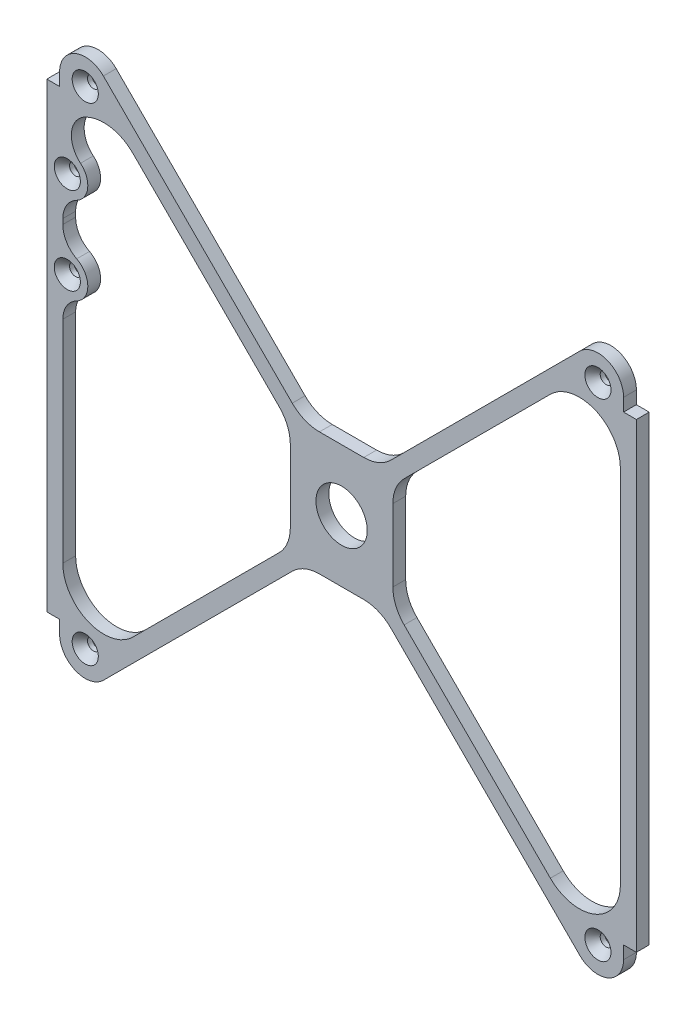
SolidWorks part; units mm, degrees
material "6061-T6 (SS)"
ref_plane "Front Plane" through (0, 0, 0) normal (0, 0, 1) x (1, 0, 0)
ref_plane "Top Plane" through (0, 0, 0) normal (0, 1, 0) x (1, 0, 0)
ref_plane "Right Plane" through (0, 0, 0) normal (1, 0, 0) x (0, 0, -1)
sketch "Sketch1" plane through (0, 0, 0) normal (0, 0, 1) x (1, 0, 0)
  line L0 (0, 0) -> (0, 73.025) construction
  line L1 (0, 0) -> (73.025, 0) construction
  line L2 (73.025, 73.025) -> (73.025, 0) construction
  line L3 (9.4347, 15.24) -> (0, 15.24)
  line L4 (12.7, 12.8926) -> (12.7, 0)
  line L5 (9.4347, 15.24) -> (59.0099, 64.8151)
  line L6 (12.7, 12.8926) -> (51.712, 51.9046)
  line L7 (69.0562, 44.7204) -> (69.0563, 0)
  line L8 (0, 73.025) -> (73.025, 73.025) construction
  line L9 (73.025, 57.15) -> (73.025, 0)
  line L10 (69.85, 60.325) -> (69.85, 57.15)
  line L11 (0, 0) -> (12.7, 0)
  line L12 (0, 15.24) -> (0, 0)
  line L13 (69.0563, 0) -> (73.025, 0)
  line L26 (69.85, 57.15) -> (73.025, 57.15)
  arc A1 (69.85, 60.325) -> (59.0099, 64.8151) centre (63.5, 60.325) ccw
  arc A2 (51.712, 51.9046) -> (69.0562, 44.7204) centre (58.8963, 44.7204) cw
  point P51 (12, 0)
  dimension "D11" = 6.35
  dimension "D5" = 10.16
  dimension "D3" = 12.7
  dimension "D6" = 3.9688
  dimension "D7" = 73.025
  dimension "D10" = 12.7
  dimension "D2" = 73.025
  dimension "D4" = 15.24
  dimension "D9" = 9.525
  dimension "D12" = 135
  dimension "D14" = 3.9688
  dimension "D8" = 15.875
extrude "Boss-Extrude1" add sketch "Sketch1" along normal blind 3.175
sketch "LOCATES-SCREW" plane through (0, 0, 3.175) normal (0, 0, 1) x (1, 0, 0)
  point P0 (63.5, 60.325)
hole_wizard "CSK for #4 Flat Head Machine Screw1" positions "Sketch10" profile "Sketch11" countersink size "#4" standard "ANSI Inch" end condition through all
sketch "Sketch10" plane through (0, 0, 3.175) normal (0, 0, 1) x (1, 0, 0)
  point P0 (63.5, 60.325)
sketch "Sketch11" plane through (63.5, 60.325, 3.175) normal (1, 0, 0) x (0, -1, 0)
  line L0 (0, 0) -> (0, 3.175)
  line L1 (0, 3.175) -> (1.4732, 3.175)
  line L2 (1.4732, 3.175) -> (1.4732, 2.0307)
  line L3 (1.4732, 2.0307) -> (3.2385, 0)
  line L5 (3.2385, 0) -> (0, 0)
  line L6 (-1.4732, 2.0307) -> (-3.2385, 0) construction
  line L11 (0, -6.35) -> (0, 107.95) construction
  dimension "Thru Hole Dia." = 2.9464
  dimension "Thru Hole Depth" = 3.175
  dimension "Near C'Sink Dia." = 6.477
  dimension "Near C'Sink Angle" = 82
mirror "Mirror1" about plane through (0, 0, 0) normal (0, 1, 0) of "CSK for #4 Flat Head Machine Screw1", "Boss-Extrude1"
mirror "Mirror2" about plane through (0, 0, 0) normal (1, 0, 0) of "Mirror1", "Boss-Extrude1", "CSK for #4 Flat Head Machine Screw1"
chamfer "COUNTERSINK" [suppressed] distance 1.27 angle 45
fillet "INTERNAL-SHARPS" radius 9.525 8 edges at (9.4347, 15.24, 1.5875) (-9.4347, 15.24, 1.5875) (12.7, -12.8926, 1.5875) (12.7, 12.8926, 1.5875) (9.4347, -15.24, 1.5875) (-9.4347, -15.24, 1.5875) (-12.7, -12.8926, 1.5875) (-12.7, 12.8926, 1.5875)
sketch "Sketch5" plane through (0, 0, 0) normal (0, 0, 1) x (1, 0, 0)
  line L0 (15.4898, 15.6824) -> (51.712, 51.9046) construction
  line L1 (69.0562, 44.7204) -> (69.0562, -44.7204) construction
  line L2 (73.025, 0) -> (54, 0) construction
  line L3 (69.0563, 12.7) -> (57.785, 12.7)
  line L4 (55.245, -10.7499) -> (55.245, 10.7499)
  line L5 (73.025, -57.15) -> (73.025, 57.15) construction
  line L6 (32.9011, 33.0937) -> (35.1462, 35.3388)
  line L7 (55.245, 10.7499) -> (32.9011, 33.0937)
  line L8 (57.785, 12.7) -> (35.1462, 35.3388)
  line L9 (69.0563, 12.7) -> (69.0563, -12.7)
  line L10 (69.0563, -12.7) -> (57.785, -12.7)
  line L11 (57.785, -12.7) -> (35.1462, -35.3388)
  line L12 (55.245, -10.7499) -> (32.9011, -33.0937)
  line L13 (32.9011, -33.0937) -> (35.1462, -35.3388)
  circle A0 centre (58.7375, 7.9375) radius 1.65 construction
  circle A1 centre (68.2625, 7.9375) radius 1.65 construction
  circle A2 centre (68.2625, -7.9375) radius 1.65 construction
  circle A3 centre (58.7375, -7.9375) radius 1.65 construction
  dimension "D1" = 3.3
  dimension "D2" = 12.7
  dimension "D3" = 15.24
  dimension "D4" = 9.525
  dimension "D5" = 15.875
  dimension "D6" = 4.7625
  dimension "D7" = 3.175
  dimension "D8" = 17.78
extrude "BRAKE-MOUNT" [suppressed] add sketch "Sketch5" along normal blind 3.175
sketch "PROJECTED-FROM-SKETCH-5" plane through (0, 0, 3.175) normal (0, 0, 1) x (1, 0, 0)
  circle A0 centre (58.7375, 7.9375) radius 1.65 construction
  circle A1 centre (58.7375, 7.9375) radius 1.65
  circle A2 centre (68.2625, 7.9375) radius 1.65 construction
  circle A3 centre (68.2625, -7.9375) radius 1.65 construction
  circle A4 centre (58.7375, -7.9375) radius 1.65 construction
  circle A5 centre (68.2625, 7.9375) radius 1.65
  circle A6 centre (68.2625, -7.9375) radius 1.65
  circle A7 centre (58.7375, -7.9375) radius 1.65
extrude "Cut-Extrude1" [suppressed] cut sketch "PROJECTED-FROM-SKETCH-5" against normal through all
fillet "Fillet1" [suppressed] radius 6.35
sketch "Sketch6" plane through (0, 0, 0) normal (0, 0, -1) x (-1, 0, 0)
  circle A0 centre (0, 0) radius 6.35
  dimension "D1" = 12.7
sketch "Sketch13" plane through (0, 0, 0) normal (0, 0, 1) x (1, 0, 0)
  line L0 (-73.025, 57.15) -> (-73.025, -57.15) construction
  line L1 (-73.025, 44.45) -> (-73.025, 12.7)
  line L2 (-73.025, 12.7) -> (-67.945, 12.7)
  line L3 (-73.025, 44.45) -> (-67.945, 44.45)
  line L4 (-69.0562, -44.7204) -> (-69.0562, 44.7204) construction
  line L6 (-69.0562, 22.737) -> (-69.0562, 34.413)
  arc A0 (-69.0562, 34.413) -> (-67.945, 44.45) centre (-67.945, 39.37) ccw
  arc A1 (-67.945, 12.7) -> (-69.0562, 22.737) centre (-67.945, 17.78) ccw
  circle A3 centre (-63.5, 60.325) radius 1.4732 construction
  point P6 (-69.0562, 38.0344)
  point P10 (-73.025, 28.575)
  point P16 (0, 0)
  point P17 (-65.2844, 38.1871)
  dimension "D1" = 31.75
  dimension "D2" = 21.59
  dimension "D3" = 31.75
  dimension "D4" = 5.08
extrude "IMU-MOUNTING" add sketch "Sketch13" along normal blind 3.175
hole_wizard "IMU-MOUNTING-HOLES" positions "Sketch14" profile "Sketch15" countersink size "#4" standard "ANSI Inch" end condition through all
sketch "Sketch14" plane through (0, 0, 3.175) normal (0, 0, 1) x (1, 0, 0)
  arc A0 (-67.945, 12.7) -> (-69.0563, 22.737) centre (-67.945, 17.78) ccw construction
  point P1 (-67.945, 17.78)
  point P7 (-67.945, 39.37)
  dimension "D1" = 21.59
sketch "Sketch15" plane through (-67.945, 17.78, 3.175) normal (1, 0, 0) x (0, -1, 0)
  line L0 (0, 0) -> (0, 3.175)
  line L1 (0, 3.175) -> (1.4732, 3.175)
  line L2 (1.4732, 3.175) -> (1.4732, 2.0307)
  line L3 (1.4732, 2.0307) -> (3.2385, 0)
  line L5 (3.2385, 0) -> (0, 0)
  line L6 (-1.4732, 2.0307) -> (-3.2385, 0) construction
  line L11 (0, -6.35) -> (0, 107.95) construction
  dimension "Thru Hole Dia." = 2.9464
  dimension "Thru Hole Depth" = 3.175
  dimension "Near C'Sink Dia." = 6.477
  dimension "Near C'Sink Angle" = 82
fillet "Fillet4" radius 6.35 4 edges at (-69.0563, 44.45, 1.5875) (-69.0563, 12.7, 1.5875) (-69.0563, 22.737, 1.5875) (-69.0563, 34.413, 1.5875)
hole_wizard "CSK for #4 Flat Head Machine Screw2" [suppressed] positions "3DSketch2" profile "Sketch17" countersink size "#4" standard "ANSI Inch"
sketch3d "3DSketch2"
  point P0 (58.7375, -7.9375, 3.175)
  point P3 (58.7375, 7.9375, 3.175)
  point P6 (68.2625, 7.9375, 3.175)
  point P9 (68.2625, -7.9375, 3.175)
sketch "Sketch17" plane through (58.7375, -7.9375, 3.175) normal (1, 0, 0) x (0, -1, 0)
  line L0 (0, 0) -> (0, 3.175)
  line L1 (0, 3.175) -> (1.4732, 3.175)
  line L2 (1.4732, 3.175) -> (1.4732, 1.5925)
  line L3 (1.4732, 1.5925) -> (2.8575, 0)
  line L5 (2.8575, 0) -> (0, 0)
  line L6 (-1.4732, 1.5925) -> (-2.8575, 0) construction
  line L11 (0, -6.35) -> (0, 107.95) construction
  dimension "Thru Hole Dia." = 2.9464
  dimension "Thru Hole Depth" = 3.175
  dimension "Near C'Sink Dia." = 5.715
  dimension "Near C'Sink Angle" = 82
extrude "MATERIAL-REMOVAL" cut sketch "Sketch6" against normal through all contours A0
equation "\"D14@Sketch1\"=\"D6@Sketch1\""
